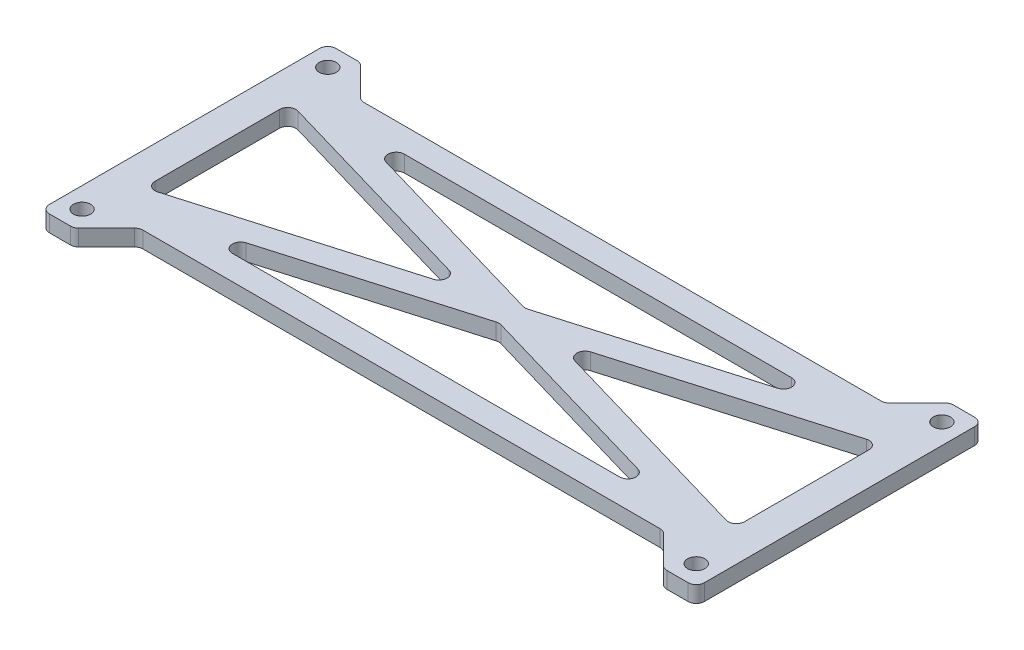
SolidWorks part; units mm, degrees
material "Thornel Mat VMA"
ref_plane "前视基准面" through (0, 0, 0) normal (0, 0, 1) x (1, 0, 0)
ref_plane "上视基准面" through (0, 0, 0) normal (0, 1, 0) x (1, 0, 0)
ref_plane "右视基准面" through (0, 0, 0) normal (1, 0, 0) x (0, 0, -1)
sketch "草图2" plane through (0, 0, 0) normal (0, 1, 0) x (1, 0, 0)
  line L0 (-36, 17.5) -> (-32, 13.5)
  line L1 (37.5, -15) -> (-37.5, -15) construction
  line L2 (37.5, -15) -> (37.5, 15) construction
  line L3 (37.5, 15) -> (-37.5, 15) construction
  line L4 (-37.5, -15) -> (-37.5, 15) construction
  line L5 (37.5, -15) -> (-37.5, 15) construction
  line L6 (37.5, 15) -> (-37.5, -15) construction
  line L7 (40, -17.5) -> (36, -17.5)
  line L8 (40, -17.5) -> (40, 17.5)
  line L9 (40, 17.5) -> (36, 17.5)
  line L10 (-40, -17.5) -> (-40, 17.5)
  line L11 (40, -17.5) -> (-40, 17.5) construction
  line L12 (40, 17.5) -> (-40, -17.5) construction
  line L17 (-32, -13.5) -> (32, -13.5)
  line L18 (-36, -17.5) -> (-32, -13.5)
  line L19 (0, 0) -> (0, 9.5652) construction
  line L20 (0, 0) -> (7.9128, 0) construction
  line L21 (36, 17.5) -> (32, 13.5)
  line L22 (36, -17.5) -> (32, -13.5)
  line L23 (-36, 17.5) -> (-40, 17.5)
  line L24 (36, -10.5) -> (-36, -10.5) construction
  line L25 (36, -10.5) -> (36, 10.5) construction
  line L26 (-32, 13.5) -> (32, 13.5)
  line L27 (36, 10.5) -> (-36, 10.5) construction
  line L28 (-36, -10.5) -> (-36, 10.5) construction
  line L29 (36, -10.5) -> (-36, 10.5) construction
  line L30 (36, 10.5) -> (-36, -10.5) construction
  line L31 (-36, -17.5) -> (-40, -17.5)
  line L32 (30.6429, 10.5) -> (0, 1.5625)
  line L33 (-30.6429, -10.5) -> (0, -1.5625)
  line L34 (-30.6429, 10.5) -> (0, 1.5625)
  line L35 (-36, 8.9375) -> (-5.3571, 0)
  line L36 (-36, 8.9375) -> (-36, -8.9375)
  line L37 (-30.6429, -10.5) -> (30.6429, -10.5)
  line L38 (36, -8.9375) -> (36, 8.9375)
  line L39 (30.6429, 10.5) -> (-30.6429, 10.5)
  line L40 (-5.3571, 0) -> (-36, -8.9375)
  line L41 (5.3571, 0) -> (36, -8.9375)
  line L42 (5.3571, 0) -> (36, 8.9375)
  line L43 (2.1429, -0.9375) -> (2.259, -0.9036)
  line L44 (0, -1.5625) -> (30.6429, -10.5)
  circle A0 centre (-37.5, 15) radius 1.05
  circle A1 centre (37.5, 15) radius 1.05
  circle A2 centre (37.5, -15) radius 1.05
  circle A3 centre (-37.5, -15) radius 1.05
  point P0 (0, 0)
  point P6 (0, 0)
  point P15 (0, 0)
  dimension "D1" = 2.1
  dimension "D2" = 2.5
  dimension "D3" = 2.5
  dimension "D4" = 75
  dimension "D5" = 30
  dimension "D6" = 27
  dimension "D7" = 4
  dimension "D8" = 45
  dimension "D9" = 64
  dimension "D10" = 3
  dimension "D12" = 3
extrude "凸台-拉伸1" add sketch "草图2" along normal blind 2
fillet "圆角1" radius 1 24 edges at (-30.6429, 1, 10.5) (30.6429, 1, 10.5) (0, 1, 1.5625) (36, 1, 8.9375) (36, 1, -8.9375) (5.3571, 1, 0) (-36, 1, -8.9375) (-36, 1, 8.9375) (-5.3571, 1, 0) (-40, 1, 17.5) (-36, 1, -17.5) (-32, 1, -13.5) (32, 1, -13.5) (36, 1, -17.5) (40, 1, -17.5) (40, 1, 17.5) (36, 1, 17.5) (32, 1, 13.5) (-32, 1, 13.5) (-36, 1, 17.5) (-30.6429, 1, -10.5) (0, 1, -1.5625) (30.6429, 1, -10.5) (-40, 1, -17.5)
